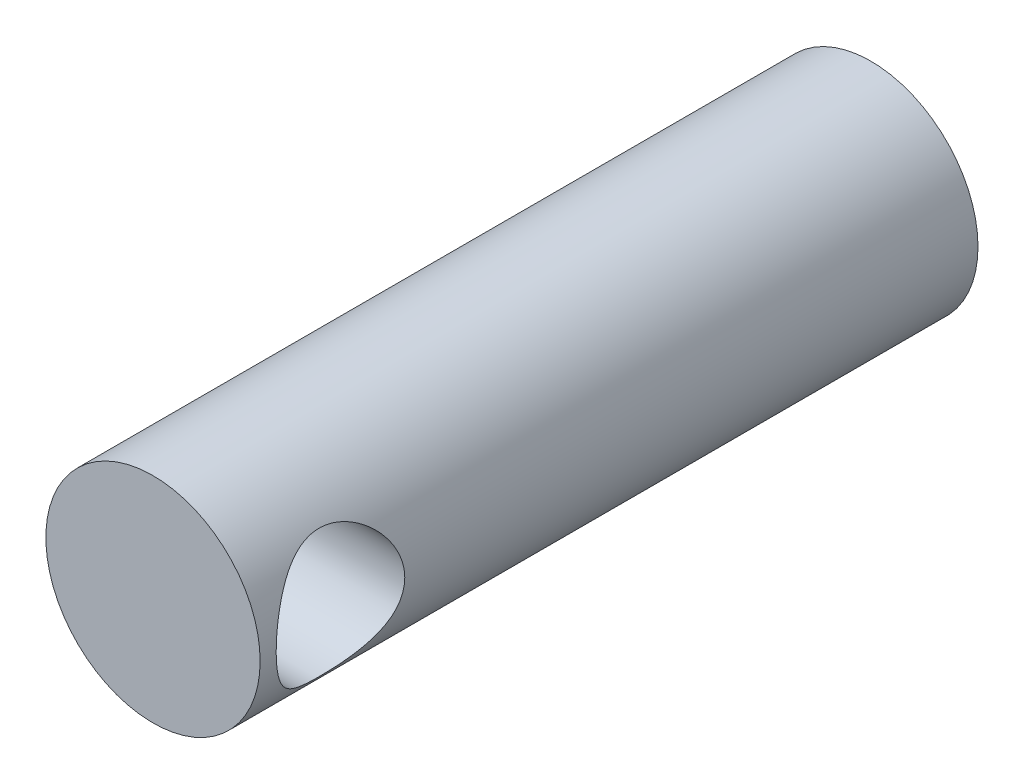
SolidWorks part; units mm, degrees
ref_plane "Plano frontal" through (0, 0, 0) normal (0, 0, 1) x (1, 0, 0)
ref_plane "Plano superior" through (0, 0, 0) normal (0, 1, 0) x (1, 0, 0)
ref_plane "Plano direito" through (0, 0, 0) normal (1, 0, 0) x (0, 0, -1)
sketch "Esboço1" plane through (0, 0, 0) normal (0, 0, 1) x (1, 0, 0)
  circle A0 centre (0, 0) radius 10
  dimension "D1" = 20
extrude "Ressalto-extrusão1" add sketch "Esboço1" along normal blind 67
sketch "Esboço3" plane through (0, 0, 0) normal (1, 0, 0) x (0, 0, -1)
  line L0 (-67, 10) -> (-67, -10) construction
  line L1 (0, 10) -> (-67, 10) construction
  circle A0 centre (-59.5, 0) radius 6
  dimension "D1" = 7.5
  dimension "D2" = 10
extrude "Corte-extrusão1" cut sketch "Esboço3" against normal mid plane 20
